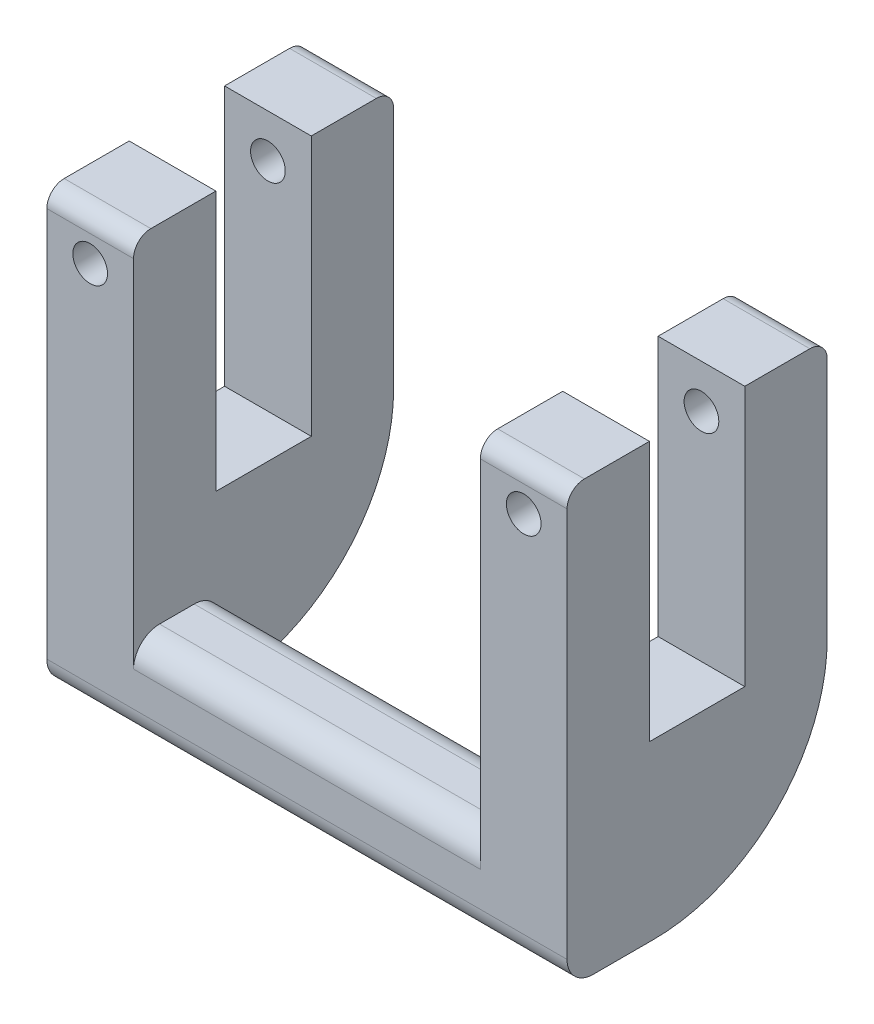
SolidWorks part; units mm, degrees
ref_plane "Front Plane" through (0, 0, 0) normal (0, 0, 1) x (1, 0, 0)
ref_plane "Top Plane" through (0, 0, 0) normal (0, 1, 0) x (1, 0, 0)
ref_plane "Right Plane" through (0, 0, 0) normal (1, 0, 0) x (0, 0, -1)
sketch "Sketch1" plane through (0, 0, 0) normal (0, 0, 1) x (1, 0, 0)
  line L0 (0, 0) -> (-40, 0)
  line L1 (-40, 0) -> (-40, 40)
  line L2 (-40, 40) -> (-50, 40)
  line L3 (-50, 40) -> (-50, -10)
  line L4 (-50, -10) -> (10, -10)
  line L5 (10, -10) -> (10, 40)
  line L6 (10, 40) -> (0, 40)
  line L7 (0, 40) -> (0, 0)
  dimension "D1" = 40
  dimension "D2" = 10
  dimension "D3" = 10
  dimension "D4" = 50
  dimension "D5" = 40
extrude "Boss-Extrude1" add sketch "Sketch1" along normal blind 30
sketch "Sketch2" plane through (10, 0, 0) normal (1, 0, 0) x (0, 0, -1)
  line L0 (-15, 40) -> (-15, -10) construction
  line L1 (-30, 40) -> (0, 40) construction
  line L2 (-30, -10) -> (0, -10) construction
  line L4 (-9.5, 70) -> (-20.5, 70)
  line L5 (-9.5, 70) -> (-9.5, 10)
  line L6 (-9.5, 10) -> (-20.5, 10)
  line L7 (-20.5, 70) -> (-20.5, 10)
  line L8 (-9.5, 70) -> (-20.5, 10) construction
  line L9 (-9.5, 10) -> (-20.5, 70) construction
  dimension "D1" = 11
  dimension "D2" = 60
extrude "Cut-Extrude1" cut sketch "Sketch2" against normal through all both and the other way through all
sketch "Sketch3" plane through (0, 0, 0) normal (0, 0, -1) x (-1, 0, 0)
  line L0 (50, -10) -> (-10, -10) construction
  line L1 (0, 0) -> (40, 0)
  line L2 (0, 0) -> (0, -10)
  line L3 (0, -10) -> (40, -10)
  line L4 (40, 0) -> (40, -10)
extrude "Cut-Extrude2" cut sketch "Sketch3" against normal blind 20
fillet "Fillet2" radius 3 4 edges at (-20, -10, 30) (-20, 0, 30) (-20, -10, 20) (-20, 0, 20)
fillet "Fillet3" radius 20 2 edges at (-45, -10, 0) (5, -10, 0)
sketch "Sketch4" plane through (0, 0, 0) normal (0, 0, -1) x (-1, 0, 0)
  line L1 (-10, 40) -> (0, 40) construction
  line L3 (-5, 40) -> (-5, 35) construction
  circle A1 centre (-5, 35) radius 2
  dimension "D1" = 5
  dimension "D2" = 4
extrude "Cut-Extrude3" cut sketch "Sketch4" against normal through all both and the other way through all
sketch "Sketch5" plane through (0, 0, 0) normal (0, 0, -1) x (-1, 0, 0)
  line L0 (45, 40) -> (45, 35) construction
  line L1 (40, 40) -> (50, 40) construction
  circle A0 centre (45, 35) radius 2
  dimension "D2" = 4
  dimension "D1" = 5
extrude "Cut-Extrude4" cut sketch "Sketch5" against normal through all both and the other way through all
fillet "Fillet4" radius 2 4 edges at (-45, 40, 0) (-45, 40, 30) (5, 40, 30) (5, 40, 0)
